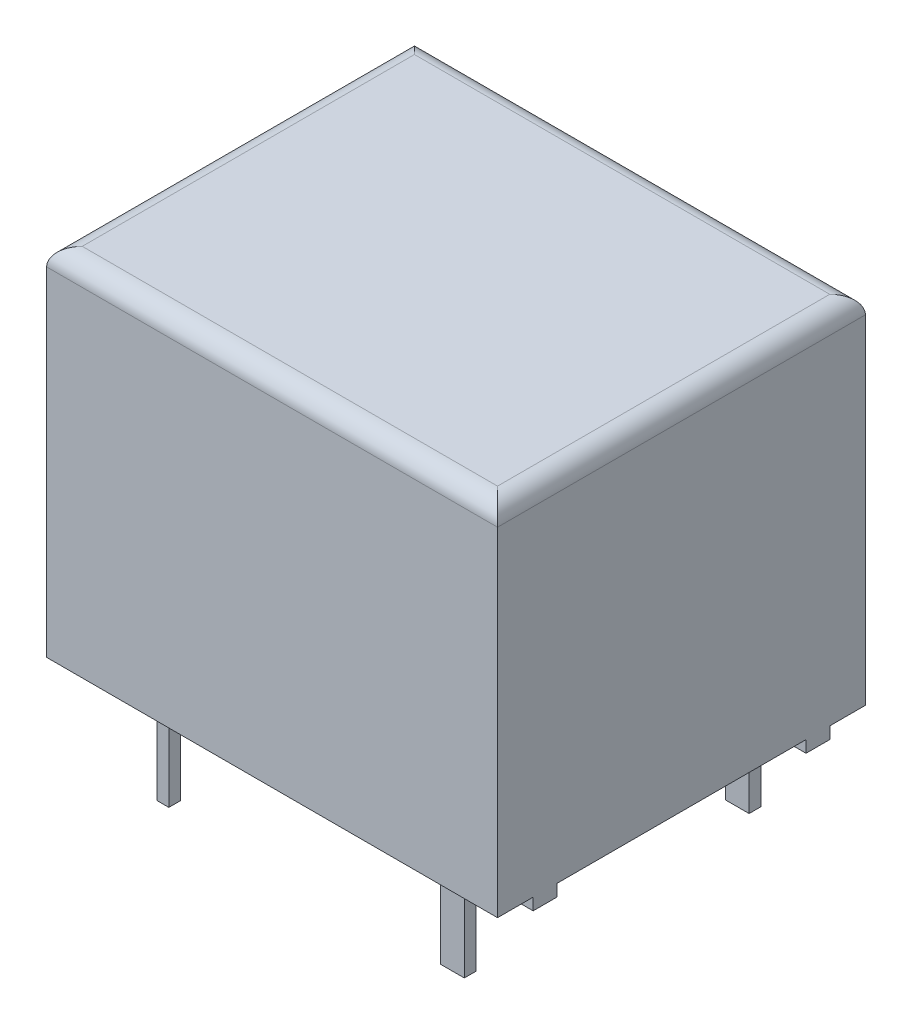
SolidWorks part; units mm, degrees
ref_plane "Front Plane" through (0, 0, 0) normal (0, 0, 1) x (1, 0, 0)
ref_plane "Top Plane" through (0, 0, 0) normal (0, 1, 0) x (1, 0, 0)
ref_plane "Right Plane" through (0, 0, 0) normal (1, 0, 0) x (0, 0, -1)
sketch "Sketch1" plane through (0, 0, 0) normal (0, 1, 0) x (1, 0, 0)
  line L1 (9.5, -7.75) -> (-9.5, -7.75)
  line L2 (9.5, -7.75) -> (9.5, 7.75)
  line L3 (9.5, 7.75) -> (-9.5, 7.75)
  line L4 (-9.5, -7.75) -> (-9.5, 7.75)
  line L5 (9.5, -7.75) -> (-9.5, 7.75) construction
  line L6 (9.5, 7.75) -> (-9.5, -7.75) construction
  point P0 (0, 0)
  dimension "D1" = 19
  dimension "D2" = 15.5
extrude "Base Extrusion" add sketch "Sketch1" along normal blind 15
sketch "Sketch2" plane through (0, 0, 0) normal (0, -1, 0) x (1, 0, 0)
  line L1 (8.525, 0) -> (-8.525, 0) construction
  line L2 (-7.95, -0.6) -> (-8.25, -0.6)
  line L3 (-7.95, -0.6) -> (-7.95, 0.6)
  line L4 (-7.95, 0.6) -> (-8.25, 0.6)
  line L6 (-8.25, -0.6) -> (-8.25, 0.6)
  line L7 (-7.95, -0.6) -> (-8.25, 0.6) construction
  line L8 (-7.95, 0.6) -> (-8.25, -0.6) construction
  line L9 (9.5, 7.75) -> (9.5, -7.75) construction
  line L10 (-6.1, 6) -> (-6.1, -6) construction
  line L11 (-6.35, -5.75) -> (-5.85, -5.75)
  line L12 (-6.35, -5.75) -> (-6.35, -6.25)
  line L13 (-6.35, -6.25) -> (-5.85, -6.25)
  line L14 (-5.85, -5.75) -> (-5.85, -6.25)
  line L15 (-6.35, -5.75) -> (-5.85, -6.25) construction
  line L16 (-6.35, -6.25) -> (-5.85, -5.75) construction
  line L17 (-6.35, 6.25) -> (-5.85, 6.25)
  line L18 (-6.35, 6.25) -> (-6.35, 5.75)
  line L19 (-6.35, 5.75) -> (-5.85, 5.75)
  line L20 (-5.85, 6.25) -> (-5.85, 5.75)
  line L21 (-6.35, 6.25) -> (-5.85, 5.75) construction
  line L22 (-6.35, 5.75) -> (-5.85, 6.25) construction
  line L24 (5.6, 5.75) -> (6.6, 5.75)
  line L25 (5.6, 5.75) -> (5.6, 6.25)
  line L26 (5.6, 6.25) -> (6.6, 6.25)
  line L27 (6.6, 5.75) -> (6.6, 6.25)
  line L28 (5.6, 5.75) -> (6.6, 6.25) construction
  line L29 (5.6, 6.25) -> (6.6, 5.75) construction
  line L30 (5.6, -6.25) -> (6.6, -6.25)
  line L31 (5.6, -6.25) -> (5.6, -5.75)
  line L32 (5.6, -5.75) -> (6.6, -5.75)
  line L33 (6.6, -6.25) -> (6.6, -5.75)
  line L34 (5.6, -6.25) -> (6.6, -5.75) construction
  line L35 (5.6, -5.75) -> (6.6, -6.25) construction
  point P0 (-8.1, 0)
  point P9 (-6.1, -6)
  point P14 (-6.1, 6)
  point P21 (-6.1, 0)
  point P22 (6.1, 6)
  point P27 (6.1, -6)
  dimension "D1" = 0.3
  dimension "D2" = 1.2
  dimension "D3" = 17.6
  dimension "D4" = 12
  dimension "D5" = 2
  dimension "D6" = 0.5
  dimension "D7" = 1
  dimension "D8" = 0.5
  dimension "D9" = 12.2
extrude "Pins" add sketch "Sketch2" along normal blind 4.4
sketch "Sketch3" plane through (0, 0, 0) normal (0, -1, 0) x (1, 0, 0)
  line L0 (-9.5, -7.75) -> (-9.5, 7.75) construction
  line L1 (-9, 5.25) -> (-9.5, 5.25)
  line L2 (-9, 5.25) -> (-9, 6.25)
  line L3 (-9, 6.25) -> (-9.5, 6.25)
  line L4 (-9.5, 5.25) -> (-9.5, 6.25)
  line L5 (-5.85, 6.25) -> (-6.35, 6.25) construction
  dimension "D1" = 0.5
  dimension "D2" = 1
extrude "Standoff" add sketch "Sketch3" along normal blind 0.5
mirror "Standoff Mirror" about plane through (0, 0, 0) normal (0, 0, 1) of "Standoff"
mirror "Standoff Mirror 2" about plane through (0, 0, 0) normal (1, 0, 0) of "Standoff Mirror", "Standoff"
fillet "Top Edge Rounds" radius 0.75 4 edges at (0, 15, -7.75) (9.5, 15, 0) (0, 15, 7.75) (-9.5, 15, 0)
